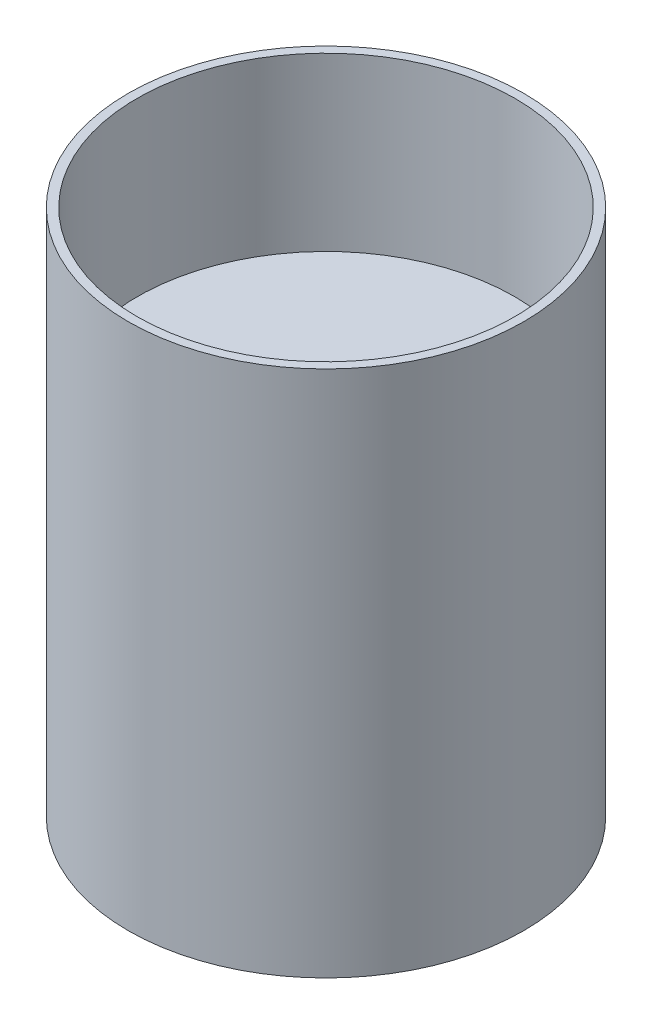
SolidWorks part; units mm, degrees
ref_plane "Front Plane" through (0, 0, 0) normal (0, 0, 1) x (1, 0, 0)
ref_plane "Top Plane" through (0, 0, 0) normal (0, 1, 0) x (1, 0, 0)
ref_plane "Right Plane" through (0, 0, 0) normal (1, 0, 0) x (0, 0, -1)
other "Configuration Table"
sketch "Sketch1" plane through (0, 0, 0) normal (0, 1, 0) x (1, 0, 0)
  circle A0 centre (0, 0) radius 45
  dimension "D1" = 90
extrude "Jar_Body" add sketch "Sketch1" along normal blind 120
sketch "Sketch2" plane through (0, 0, 0) normal (0, 1, 0) x (1, 0, 0)
  circle A0 centre (0, 0) radius 43
  dimension "D1" = 86
extrude "Jar_Cavity" cut sketch "Sketch2" along normal blind 120 from offset 3
sketch "Sketch3" plane through (0, 0, 0) normal (0, 1, 0) x (1, 0, 0)
  circle A0 centre (0, 0) radius 42.9
extrude "Water_Visual" add sketch "Sketch3" along normal blind 78 from offset 3 separate body
equation "\"out_D\"= 90.0   'ASSUMPTION: Output jar diameter (PDF fallback)"
equation "\"out_H\"= 120.0   'ASSUMPTION: Output jar height (PDF fallback)"
equation "\"jar_wall\"= 2.0   'ASSUMPTION: Jar wall thickness (designer choice)"
equation "\"jar_floor\"= 3.0   'ASSUMPTION: Jar floor thickness (designer choice)"
equation "\"D1@Sketch1\" = \"out_D\""
equation "\"D1@Jar_Body\" = \"out_H\""
equation "\"D1@Sketch2\" = \"out_D\" - 2 * \"jar_wall\""
